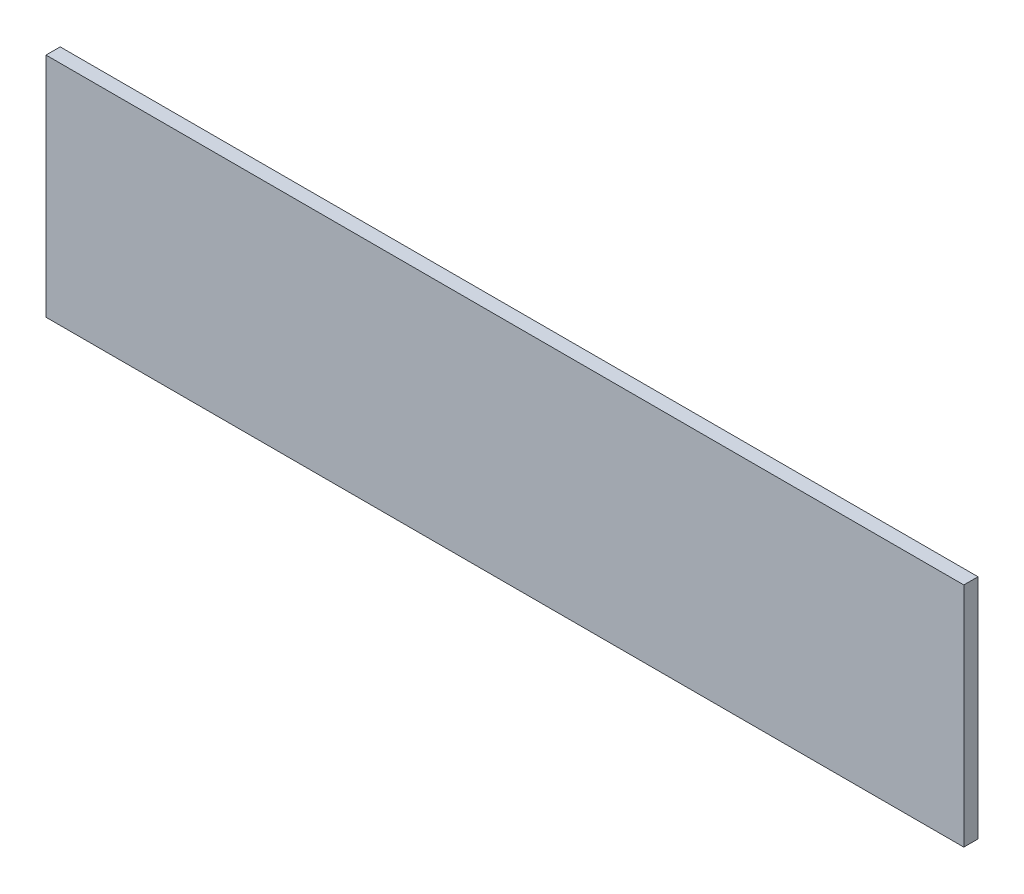
SolidWorks part; units mm, degrees
material "Acrylic (Medium-high impact)"
ref_plane "Front Plane" through (0, 0, 0) normal (0, 0, 1) x (1, 0, 0)
ref_plane "Top Plane" through (0, 0, 0) normal (0, 1, 0) x (1, 0, 0)
ref_plane "Right Plane" through (0, 0, 0) normal (1, 0, 0) x (0, 0, -1)
sketch "Sketch1" plane through (0, 0, 0) normal (0, 0, 1) x (1, 0, 0)
  line L1 (48.5, -12) -> (-48.5, -12)
  line L2 (48.5, -12) -> (48.5, 12)
  line L3 (48.5, 12) -> (-48.5, 12)
  line L4 (-48.5, -12) -> (-48.5, 12)
  line L5 (48.5, -12) -> (-48.5, 12) construction
  line L6 (48.5, 12) -> (-48.5, -12) construction
  point P0 (0, 0)
  dimension "D1" = 97
  dimension "D2" = 24
extrude "Boss-Extrude1" add sketch "Sketch1" along normal blind 1.5
